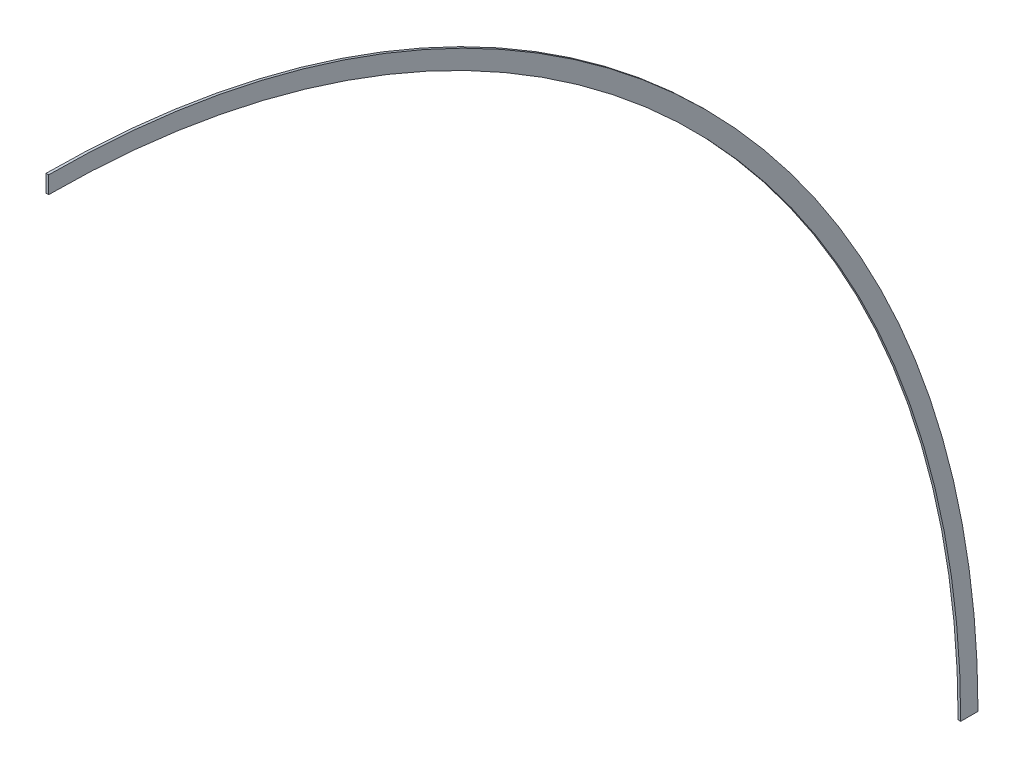
SolidWorks part; units mm, degrees
material "Galvanized Steel"
ref_plane "Front Plane" through (0, 0, 0) normal (0, 0, 1) x (1, 0, 0)
ref_plane "Top Plane" through (0, 0, 0) normal (0, 1, 0) x (1, 0, 0)
ref_plane "Right Plane" through (0, 0, 0) normal (1, 0, 0) x (0, 0, -1)
sketch "Sketch1" plane through (0, 0, 0) normal (1, 0, 0) x (0, 0, -1)
  line L0 (0, 1057) -> (0, 1077)
  line L1 (1057, 0) -> (1077, 0)
  arc A0 (1077, 0) -> (0, 1077) centre (0, 0) ccw
  arc A1 (1057, 0) -> (0, 1057) centre (0, 0) ccw
  dimension "D1" = 2114
  dimension "D2" = 20
extrude "Boss-Extrude1" add sketch "Sketch1" along normal blind 3
